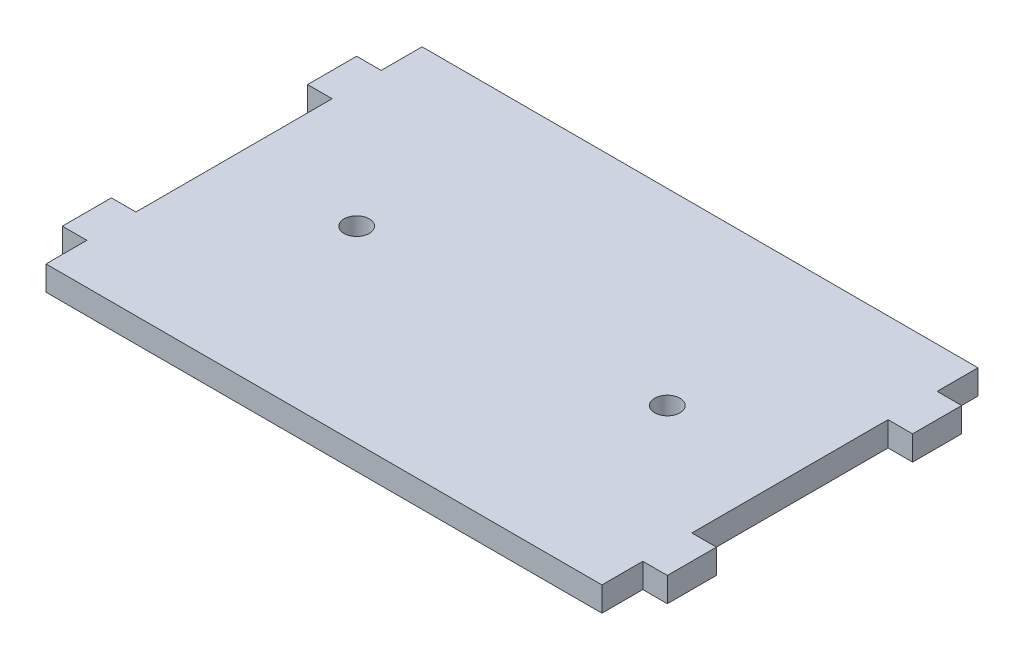
SolidWorks part; units mm, degrees
ref_plane "Front Plane" through (0, 0, 0) normal (0, 0, 1) x (1, 0, 0)
ref_plane "Top Plane" through (0, 0, 0) normal (0, 1, 0) x (1, 0, 0)
ref_plane "Right Plane" through (0, 0, 0) normal (1, 0, 0) x (0, 0, -1)
sketch "Sketch1" plane through (0, 0, 0) normal (0, 1, 0) x (1, 0, 0)
  line L0 (0, 0) -> (95.7524, 0) construction
  line L1 (0, 0) -> (0, 99.6875) construction
  line L2 (-34, 23) -> (34, 23)
  line L3 (34, 23) -> (34, 18)
  line L4 (34, 18) -> (37, 18)
  line L5 (37, 18) -> (37, 12)
  line L6 (37, 12) -> (34, 12)
  line L7 (34, 12) -> (34, -12)
  line L8 (37, -12) -> (34, -12)
  line L9 (37, -18) -> (37, -12)
  line L10 (34, -18) -> (37, -18)
  line L11 (34, -23) -> (34, -18)
  line L12 (-34, -23) -> (34, -23)
  line L13 (-34, -23) -> (-34, -18)
  line L14 (-34, -18) -> (-37, -18)
  line L15 (-37, -18) -> (-37, -12)
  line L16 (-37, -12) -> (-34, -12)
  line L17 (-34, 12) -> (-34, -12)
  line L18 (-37, 12) -> (-34, 12)
  line L19 (-37, 18) -> (-37, 12)
  line L20 (-34, 18) -> (-37, 18)
  line L21 (-34, 23) -> (-34, 18)
  circle A0 centre (19, 0) radius 1.55
  circle A1 centre (-19, 0) radius 1.55
  point P12 (34, 0)
  point P18 (0, -23)
  point P27 (0, 23)
  dimension "D6" = 3.1
  dimension "D7" = 38
  dimension "D1" = 6
  dimension "D2" = 3
  dimension "D3" = 12
  dimension "D4" = 68
  dimension "D5" = 46
extrude "Boss-Extrude1" add sketch "Sketch1" along normal blind 3
